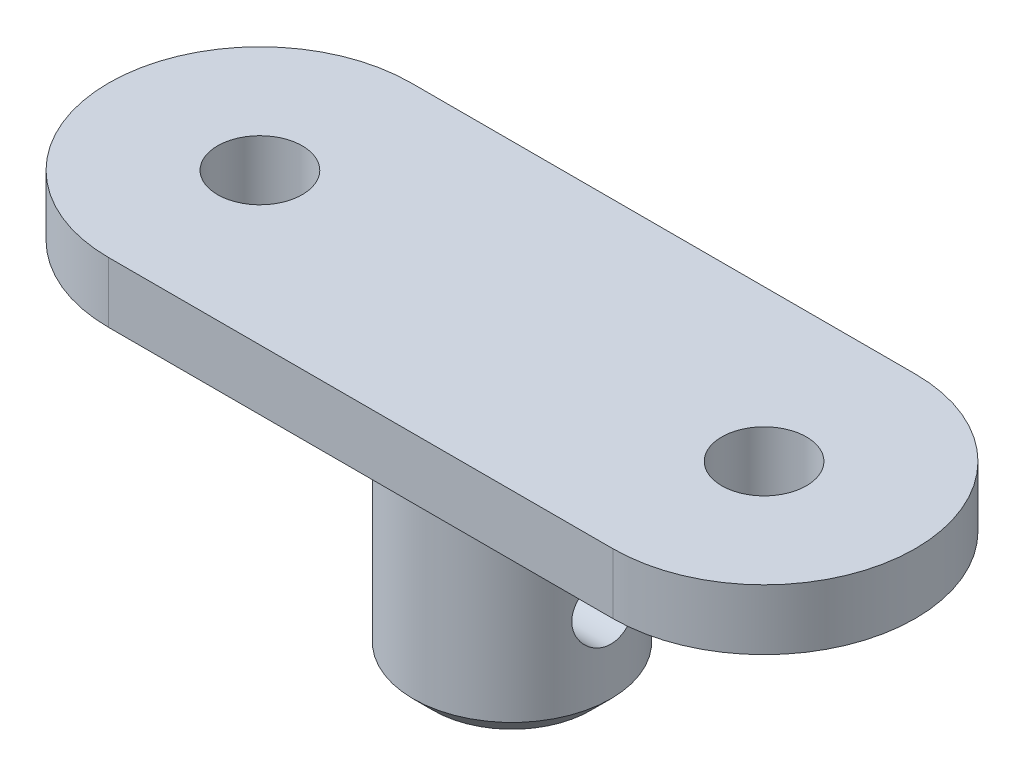
SolidWorks part; units mm, degrees
material "6061 合金"
ref_plane "前视基准面" through (0, 0, 0) normal (0, 0, 1) x (1, 0, 0)
ref_plane "上视基准面" through (0, 0, 0) normal (0, 1, 0) x (1, 0, 0)
ref_plane "右视基准面" through (0, 0, 0) normal (1, 0, 0) x (0, 0, -1)
sketch "草图1" plane through (0, 0, 0) normal (0, 1, 0) x (1, 0, 0)
  circle A0 centre (0, 0) radius 4.9
  dimension "D1" = 9.8
extrude "凸台-拉伸1" add sketch "草图1" along normal blind 15
ref_plane "基准面1" through (4.9, 0, 0) normal (1, 0, 0) x (0, 0, -1)
hole_wizard "M4 螺纹孔1" positions "草图2" profile "草图3" tap size "M4" standard "GB" end condition through all
sketch "草图2" plane through (4.9, 0, 0) normal (1, 0, 0) x (0, 0, -1)
  line L0 (-4.9, 0) -> (4.9, 0) construction
  point P0 (0, 5)
  dimension "D1" = 5
sketch "草图3" plane through (4.9, 5, 0) normal (0, 1, 0) x (0, 0, -1)
  line L0 (0, 0) -> (0, 9.8)
  line L1 (0, 9.8) -> (1.65, 9.8)
  line L2 (1.65, 9.8) -> (1.65, 0)
  line L5 (1.65, 0) -> (0, 0)
  line L11 (0, -6.35) -> (0, 107.95) construction
  dimension "通孔螺纹孔钻头直径" = 3.3
  dimension "通孔螺纹孔钻头深度" = 9.8
cosmetic thread "孔螺蚊线3" parameters "D2"=4
chamfer "倒角1" distance 1 angle 45 1 edges at (0, 0, 4.9)
sketch "草图6" plane through (0, 15, 0) normal (0, 1, 0) x (1, 0, 0)
  line L0 (-12.5, 0) -> (12.5, 0) construction
  line L1 (-12.5, 7.5) -> (12.5, 7.5)
  line L2 (-12.5, -7.5) -> (12.5, -7.5)
  arc A0 (-12.5, 7.5) -> (-12.5, -7.5) centre (-12.5, 0) ccw
  arc A1 (12.5, -7.5) -> (12.5, 7.5) centre (12.5, 0) ccw
  circle A3 centre (-12.5, 0) radius 2.1
  circle A4 centre (12.5, 0) radius 2.1
  point P2 (0, 0)
  point P14 (0, 0)
  dimension "D2" = 4.2
  dimension "D1" = 25
  dimension "D3" = 15
extrude "凸台-拉伸2" add sketch "草图6" against normal blind 3
